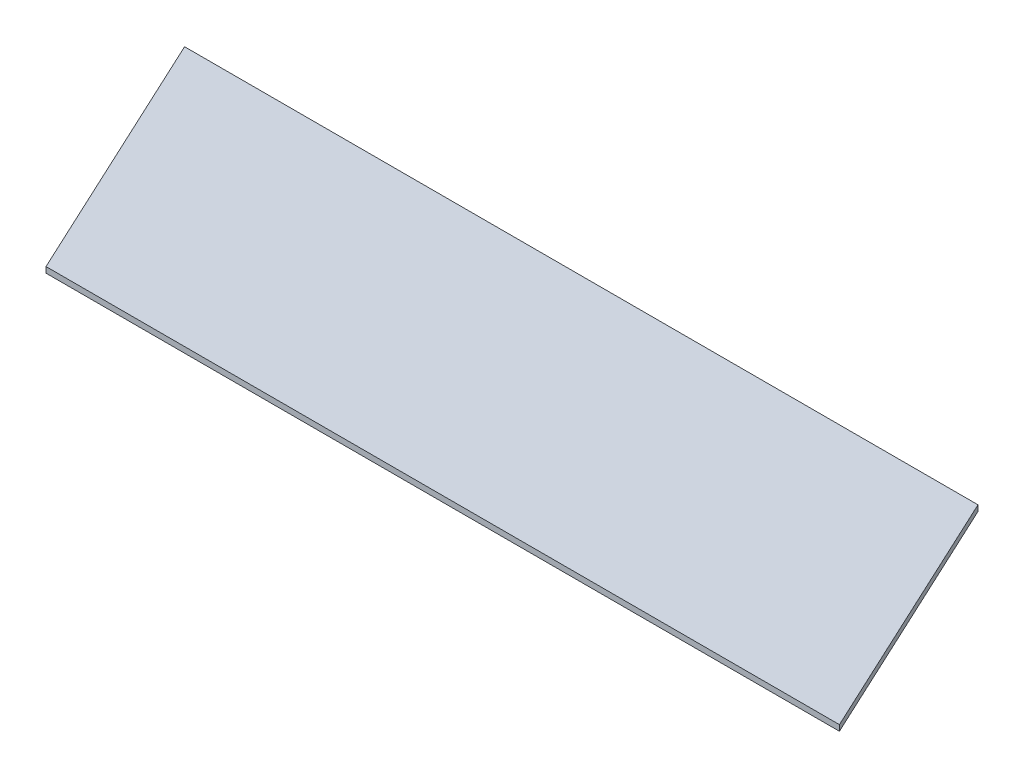
SolidWorks part; units mm, degrees
ref_plane "Front Plane" through (0, 0, 0) normal (0, 0, 1) x (1, 0, 0)
ref_plane "Top Plane" through (0, 0, 0) normal (0, 1, 0) x (1, 0, 0)
ref_plane "Right Plane" through (0, 0, 0) normal (1, 0, 0) x (0, 0, -1)
sketch "Sketch1" plane through (0, 0, 0) normal (0, 1, 0) x (1, 0, 0)
  line L0 (0, 0) -> (55, 0)
  line L2 (63.3935, -18) -> (8.3935, -18)
  line L3 (0, 0) -> (8.3935, -18)
  line L5 (55, 0) -> (63.3935, -18)
  dimension "D1" = 65
  dimension "D4" = 18
  dimension "D5" = 55
extrude "Boss-Extrude1" add sketch "Sketch1" along normal blind 0.4
